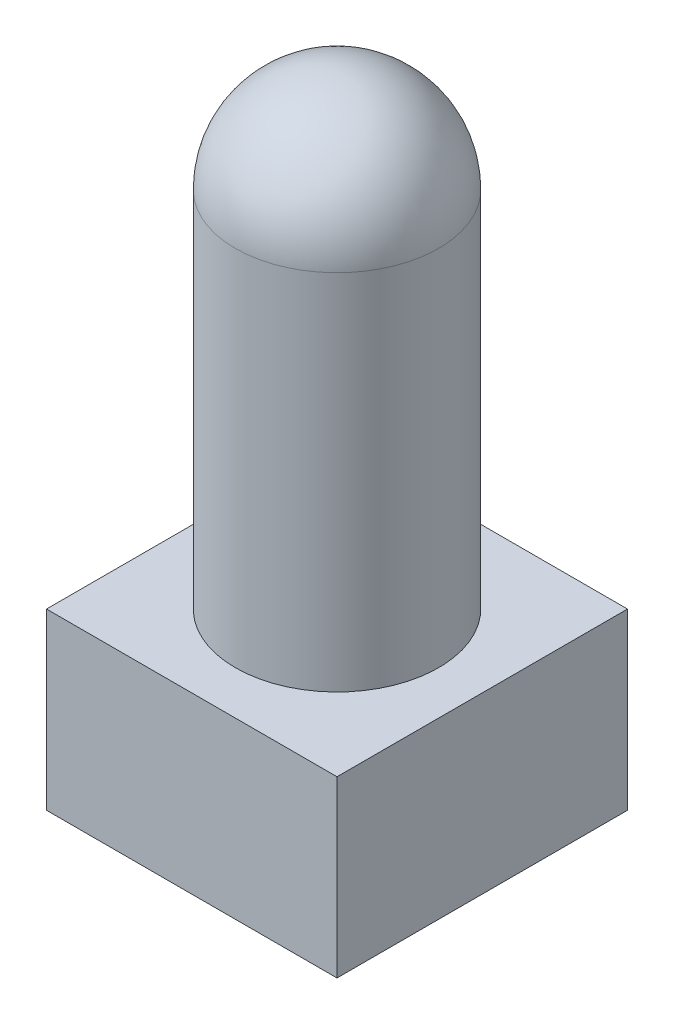
SolidWorks part; units mm, degrees
ref_plane "Front" through (0, 0, 0) normal (0, 0, 1) x (1, 0, 0)
ref_plane "Top" through (0, 0, 0) normal (0, 1, 0) x (1, 0, 0)
ref_plane "Right" through (0, 0, 0) normal (1, 0, 0) x (0, 0, -1)
sketch "Sketch1" plane through (0, 0, 0) normal (0, 1, 0) x (1, 0, 0)
  circle A0 centre (0, 0) radius 1.75
  dimension "D1" = 3.5
extrude "Boss-Extrude1" add sketch "Sketch1" along normal blind 11
fillet "Fillet1" radius 1.75 1 edges at (0, 11, 1.75)
sketch "Sketch3" plane through (0, 0, 0) normal (0, -1, 0) x (1, 0, 0)
  line L1 (-2.5, -2.5) -> (2.5, -2.5)
  line L2 (-2.5, -2.5) -> (-2.5, 2.5)
  line L3 (-2.5, 2.5) -> (2.5, 2.5)
  line L4 (2.5, -2.5) -> (2.5, 2.5)
  line L5 (-2.5, -2.5) -> (2.5, 2.5) construction
  line L6 (-2.5, 2.5) -> (2.5, -2.5) construction
  point P0 (0, 0)
  dimension "D1" = 5
extrude "Boss-Extrude2" add sketch "Sketch3" against normal blind 3
